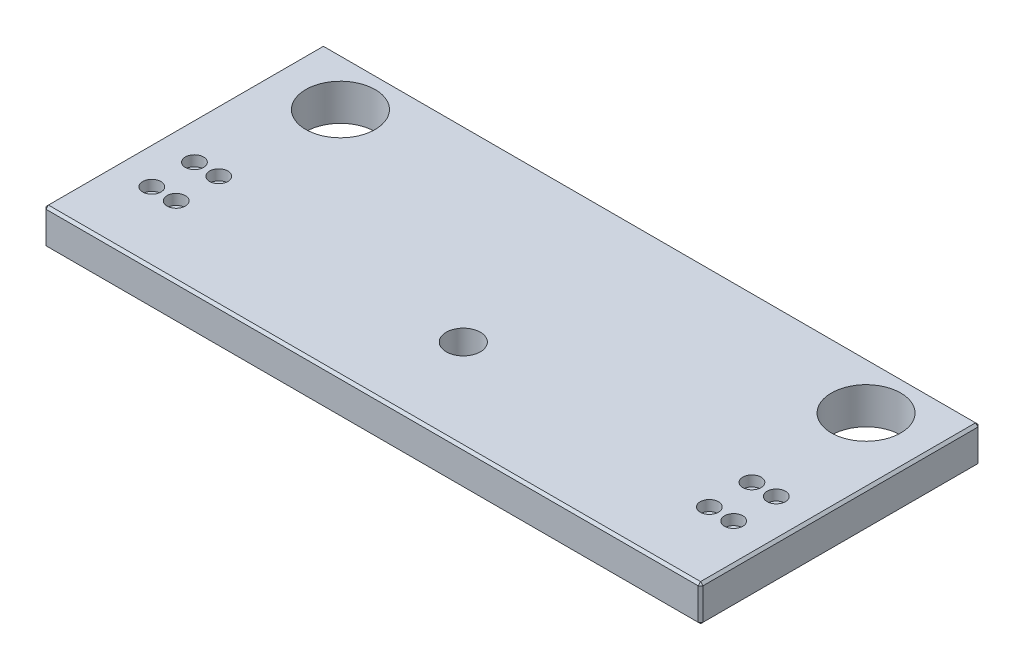
SolidWorks part; units mm, degrees
material "Plain Carbon Steel"
ref_plane "Front Plane" through (0, 0, 0) normal (0, 0, 1) x (1, 0, 0)
ref_plane "Top Plane" through (0, 0, 0) normal (0, 1, 0) x (1, 0, 0)
ref_plane "Right Plane" through (0, 0, 0) normal (1, 0, 0) x (0, 0, -1)
sketch "Sketch2" plane through (0, 0, 0) normal (0, 1, 0) x (1, 0, 0)
  line L1 (-270, -75) -> (270, -75)
  line L2 (-270, -75) -> (-270, 75)
  line L3 (-270, 75) -> (270, 75)
  line L4 (270, -75) -> (270, 75)
  line L5 (-270, -75) -> (270, 75) construction
  line L6 (-270, 75) -> (270, -75) construction
  point P0 (0, 0)
  dimension "D1" = 540
  dimension "D2" = 150
extrude "Boss-Extrude1" add sketch "Sketch2" along normal blind 30
sketch "Sketch5" plane through (0, 0, 0) normal (0, -1, 0) x (-1, 0, 0)
  line L4 (-270, 75) -> (-270, -75)
  line L5 (270, 75) -> (-270, 75)
  line L6 (270, -75) -> (270, 75)
  line L7 (-270, -75) -> (270, -75)
  line L8 (-270, 75) -> (-270, -75) construction
  line L9 (270, 75) -> (-270, 75) construction
  line L10 (270, -75) -> (270, 75) construction
  line L11 (-270, -75) -> (270, -75) construction
  dimension "D1" = 0
sketch "Sketch3" plane through (0, 0, -75) normal (0, 0, -1) x (-1, 0, 0)
  line L4 (-270, 0) -> (270, 0)
  line L5 (-270, 30) -> (-270, 0)
  line L6 (270, 30) -> (-270, 30)
  line L7 (270, 0) -> (270, 30)
  line L8 (-270, 0) -> (270, 0)
  line L9 (-270, 30) -> (-270, 0)
  line L10 (270, 30) -> (-270, 30)
  line L11 (270, 0) -> (270, 30)
  dimension "D1" = 0
extrude "Boss-Extrude2" add sketch "Sketch3" along normal blind 80
sketch "Sketch6" plane through (0, 0, 0) normal (0, -1, 0) x (-1, 0, 0)
  line L2 (270, 155) -> (-270, 155) construction
  circle A0 centre (-216, 115) radius 28.5
  dimension "D1" = 57
  dimension "D2" = 40
  dimension "D3" = 216
extrude "Cut-Extrude1" cut sketch "Sketch6" against normal through all
mirror "Mirror1" about plane through (0, 0, 0) normal (1, 0, 0) of "Cut-Extrude1"
chamfer "Chamfer1" distance 2 angle 45 12 edges at (270, 30, -40) (270, 0, -40) (0, 30, -155) (270, 15, -155) (0, 0, -155) (-270, 30, -40) (-270, 15, -155) (-270, 0, -40) (270, 15, 75) (0, 30, 75) (-270, 15, 75) (0, 0, 75)
hole_wizard "M30x2.0 Tapped Hole1" positions "Sketch10" profile "Sketch9" tap size "M30x2.0" standard "ISO" end condition through all
sketch "Sketch10" plane through (0, 30, 0) normal (0, 1, 0) x (1, 0, 0)
  point P0 (0, 0)
sketch "Sketch9" plane through (0, 30, 0) normal (1, 0, 0) x (0, 0, 1)
  line L0 (0, 0) -> (0, 30)
  line L1 (0, 30) -> (14, 30)
  line L2 (14, 30) -> (14, 0)
  line L5 (14, 0) -> (0, 0)
  line L11 (0, -6.35) -> (0, 107.95) construction
  dimension "Thru Tap Drill Dia." = 28
  dimension "Thru Tap Drill Depth" = 30
cosmetic thread "Hole Thread1"
hole_wizard "CBORE for M8 Hex Socket Head Cap Screw1" positions "Sketch13" profile "Sketch12" counterbore size "M8" standard "ISO" end condition through all
sketch "Sketch13" plane through (0, 30, 0) normal (0, 1, 0) x (1, 0, 0)
  point P0 (-238.5, 17.5)
  point P3 (-218.5, 17.5)
  point P6 (-238.5, -17.5)
  point P9 (-218.5, -17.5)
  point P12 (218.5, 18.7)
  point P15 (238.5, 18.7)
  point P18 (218.5, -16.3)
  point P21 (238.5, -16.3)
sketch "Sketch12" plane through (-238.5, 30, -17.5) normal (1, 0, 0) x (0, 0, 1)
  line L0 (0, 0) -> (0, 30)
  line L1 (0, 30) -> (4.2, 30)
  line L3 (4.2, 30) -> (4.2, 8.6)
  line L4 (4.2, 8.6) -> (7.5, 8.6)
  line L5 (7.5, 8.6) -> (7.5, 0)
  line L7 (7.5, 0) -> (0, 0)
  line L11 (0, -6.35) -> (0, 107.95) construction
  dimension "Thru Hole Dia." = 8.4
  dimension "Thru Hole Depth" = 30
  dimension "C'Bore Dia." = 15
  dimension "C'Bore Depth" = 8.6
